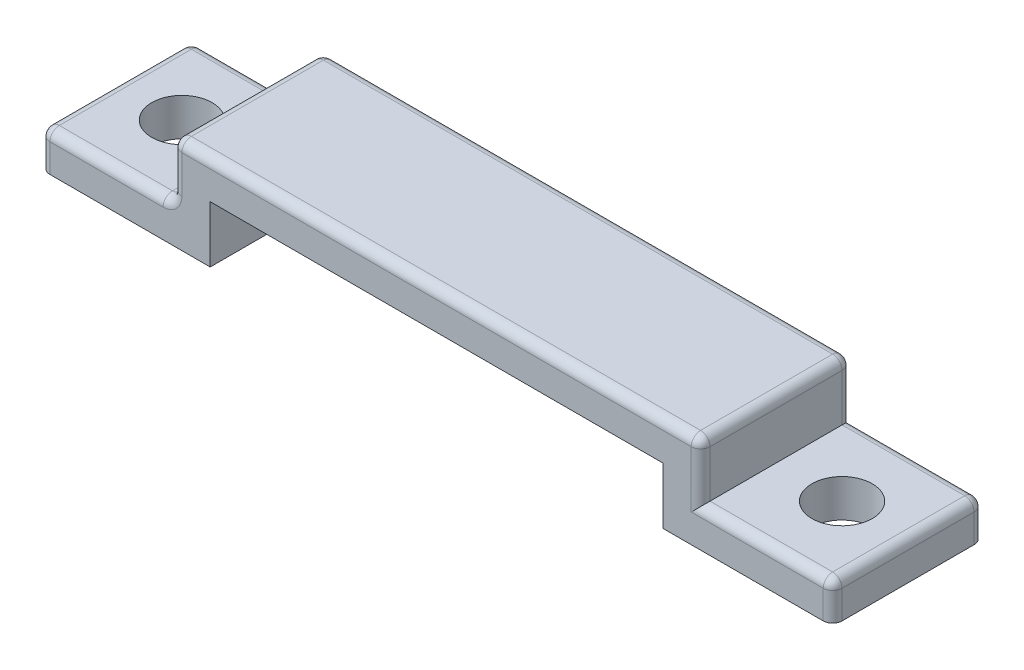
SolidWorks part; units mm, degrees
ref_plane "Ebene vorne" through (0, 0, 0) normal (0, 0, 1) x (1, 0, 0)
ref_plane "Ebene oben" through (0, 0, 0) normal (0, 1, 0) x (1, 0, 0)
ref_plane "Ebene rechts" through (0, 0, 0) normal (1, 0, 0) x (0, 0, -1)
sketch "Skizze1" plane through (0, 0, 0) normal (0, 0, 1) x (1, 0, 0)
  line L0 (0, 0) -> (0, 14.8704) construction
  line L1 (-21, 0) -> (-12, 0)
  line L2 (-12, 0) -> (-12, 3)
  line L3 (-12, 3) -> (12, 3)
  line L4 (-21, 0) -> (-21, 2)
  line L5 (-21, 2) -> (-14, 2)
  line L6 (-14, 2) -> (-14, 5)
  line L7 (-14, 5) -> (14, 5)
  line L8 (14, 2) -> (14, 5)
  line L9 (21, 2) -> (14, 2)
  line L10 (21, 0) -> (21, 2)
  line L11 (12, 0) -> (12, 3)
  line L12 (21, 0) -> (12, 0)
  point P12 (0, 5)
  point P16 (0, 3)
  dimension "D1" = 24
  dimension "D2" = 2
  dimension "D3" = 7
  dimension "D4" = 2
  dimension "D5" = 3
  dimension "D6" = 2
extrude "Grundkörper" add sketch "Skizze1" along normal blind 8
sketch "Skizze2" plane through (0, 2, 0) normal (0, 1, 0) x (1, 0, 0)
  line L0 (-21, -4) -> (25.2368, -4) construction
  line L1 (-21, -8) -> (-21, 0) construction
  line L2 (0, 0) -> (0, -9.5436) construction
  circle A0 centre (-17.5, -4) radius 1.6
  circle A1 centre (17.5, -4) radius 1.6
  dimension "D1" = 3.2
  dimension "D2" = 35
extrude "Bohrung_Befestigung" cut sketch "Skizze2" against normal through all
fillet "Verrundung1" radius 0.5 19 edges at (-14, 3.5, 8) (-14, 3.5, 0) (-21, 1, 0) (-21, 1, 8) (21, 1, 8) (21, 1, 0) (21, 2, 4) (17.5, 2, 0) (17.5, 2, 8) (14, 3.5, 8) (14, 3.5, 0) (14, 5, 4) (0, 5, 0) (0, 5, 8) (-14, 5, 4) (-14, 2, 4) (-17.5, 2, 8) (-21, 2, 4) (-17.5, 2, 0)
